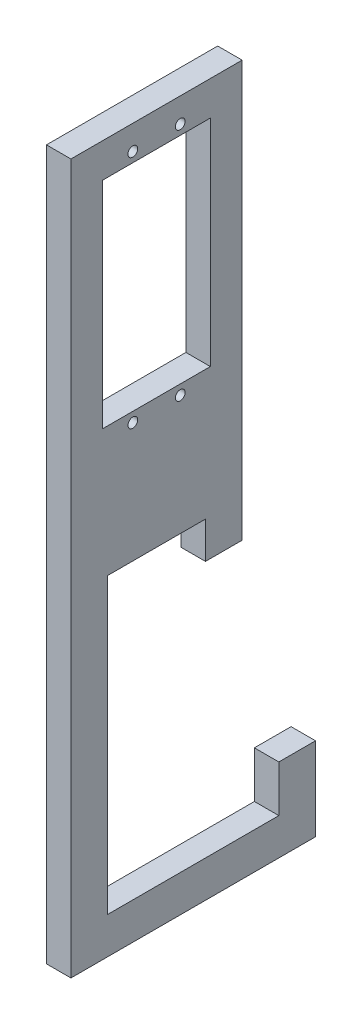
SolidWorks part; units mm, degrees
material "Polylactic Acid"
ref_plane "Front Plane" through (0, 0, 0) normal (0, 0, 1) x (1, 0, 0)
ref_plane "Top Plane" through (0, 0, 0) normal (0, 1, 0) x (1, 0, 0)
ref_plane "Right Plane" through (0, 0, 0) normal (1, 0, 0) x (0, 0, -1)
sketch "Sketch1" plane through (0, 0, 0) normal (1, 0, 0) x (0, 0, -1)
  line L0 (-4.85, -24) -> (4.85, -24) construction
  line L1 (-11, 22) -> (11, 22)
  line L2 (-11, 22) -> (-11, -22)
  line L3 (-11, -22) -> (11, -22)
  line L4 (11, 22) -> (11, -22)
  line L5 (-4.85, -24) -> (-4.85, 24) construction
  line L7 (-17.5, 29) -> (17.5, 29)
  line L8 (-17.5, 29) -> (-17.5, -41)
  line L9 (-17.5, -41) -> (17.5, -41)
  line L10 (17.5, 29) -> (17.5, -41)
  circle A0 centre (-4.85, -24) radius 1
  circle A1 centre (4.85, -24) radius 1
  circle A2 centre (4.85, 24) radius 1
  circle A3 centre (-4.85, 24) radius 1
  point P4 (0, 22)
  point P6 (-11, 0)
  point P9 (0, -24)
  point P11 (0, -22)
  point P20 (-4.85, 0)
  point P25 (0, 29)
  dimension "D7" = 2
  dimension "D1" = 22
  dimension "D2" = 44
  dimension "D3" = 9.7
  dimension "D4" = 48
  dimension "D8" = 7
  dimension "D9" = 35
  dimension "D10" = 70
  dimension "D5" = 2
  dimension "D6" = 2
extrude "Boss-Extrude1" add sketch "Sketch1" along normal mid plane 5
sketch "Sketch2" plane through (0, 0, 0) normal (1, 0, 0) x (0, 0, -1)
  line L0 (17.5, -41) -> (17.5, -56)
  line L1 (17.5, -56) -> (10, -56)
  line L2 (10, -56) -> (10, -48.5)
  line L3 (10, -48.5) -> (-10, -48.5)
  line L4 (-10, -48.5) -> (-10, -108.5)
  line L6 (32.5, -99) -> (32.5, -116)
  line L7 (32.5, -116) -> (-17.5, -116)
  line L8 (-17.5, -116) -> (-17.5, -41)
  line L9 (-17.5, -41) -> (17.5, -41)
  line L10 (-10, -108.5) -> (25, -108.5)
  line L11 (25, -108.5) -> (25, -99)
  line L12 (25, -99) -> (32.5, -99)
  point P3 (0, 0)
  point P16 (0, 0)
  dimension "D1" = 7.5
  dimension "D2" = 17
  dimension "D3" = 7.5
  dimension "D4" = 7.5
  dimension "D5" = 15
  dimension "D6" = 75
  dimension "D7" = 50
  dimension "D8" = 7.5
  dimension "D9" = 7.5
extrude "Boss-Extrude2" add sketch "Sketch2" along normal up to surface and the other way up to surface
equation "\"D3@Sketch2\"=\"D1@Sketch2\""
equation "\"D4@Sketch2\"=\"D1@Sketch2\""
equation "\"D8@Sketch2\"=\"D1@Sketch2\""
equation "\"D9@Sketch2\"=\"D1@Sketch2\""
